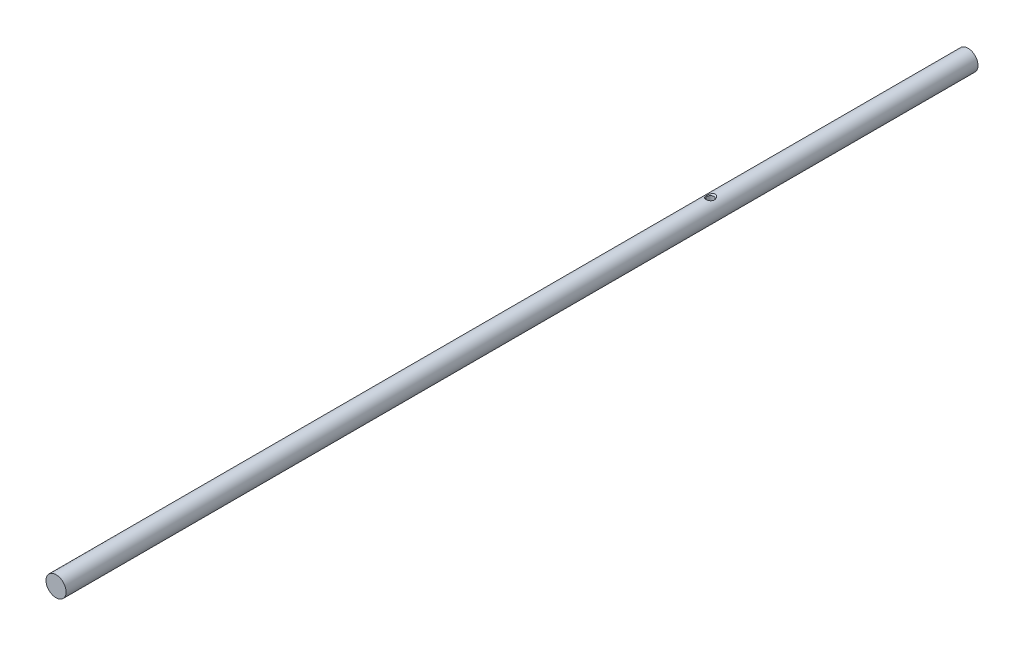
SolidWorks part; units mm, degrees
material "Plain Carbon Steel"
ref_plane "Front Plane" through (0, 0, 0) normal (0, 0, 1) x (1, 0, 0)
ref_plane "Top Plane" through (0, 0, 0) normal (0, 1, 0) x (1, 0, 0)
ref_plane "Right Plane" through (0, 0, 0) normal (1, 0, 0) x (0, 0, -1)
sketch "Sketch1" plane through (0, 0, 0) normal (0, 0, 1) x (1, 0, 0)
  circle A0 centre (0, 0) radius 4.7625
  dimension "D1" = 9.525
extrude "Boss-Extrude1" add sketch "Sketch1" along normal blind 431.8
hole_wizard "1/8 (0.125) Press Dowel Hole1" positions "3DSketch1" profile "Sketch3" hole size "1/8" standard "ANSI Inch"
sketch3d "3DSketch1"
  line L0 (0, 0, 121.92) -> (0, 4.7625, 121.92) construction
  line L1 (0, 0, 0) -> (0, 0, 431.8) construction
  line L2 (0, 0, 431.8) -> (0, 0, 0) construction
  point P0 (0, 0, 121.92)
  point P2 (0, 4.7625, 121.92)
  dimension "D1" = 121.92
sketch "Sketch3" plane through (0, 4.7625, 121.92) normal (1, 0, 0) x (0, 0, 1)
  line L0 (0, 0) -> (0, 9.525)
  line L1 (0, 9.525) -> (1.5875, 9.525)
  line L2 (1.5875, 9.525) -> (1.5875, 0.635)
  line L3 (1.5875, 0.635) -> (2.2225, 0)
  line L5 (2.2225, 0) -> (0, 0)
  line L6 (-1.5875, 0.635) -> (-2.2225, 0) construction
  line L11 (0, -6.35) -> (0, 107.95) construction
  dimension "Thru Hole Dia." = 3.175
  dimension "Thru Hole Depth" = 9.525
  dimension "Near C'Sink Dia." = 4.445
  dimension "Near C'Sink Angle" = 90
